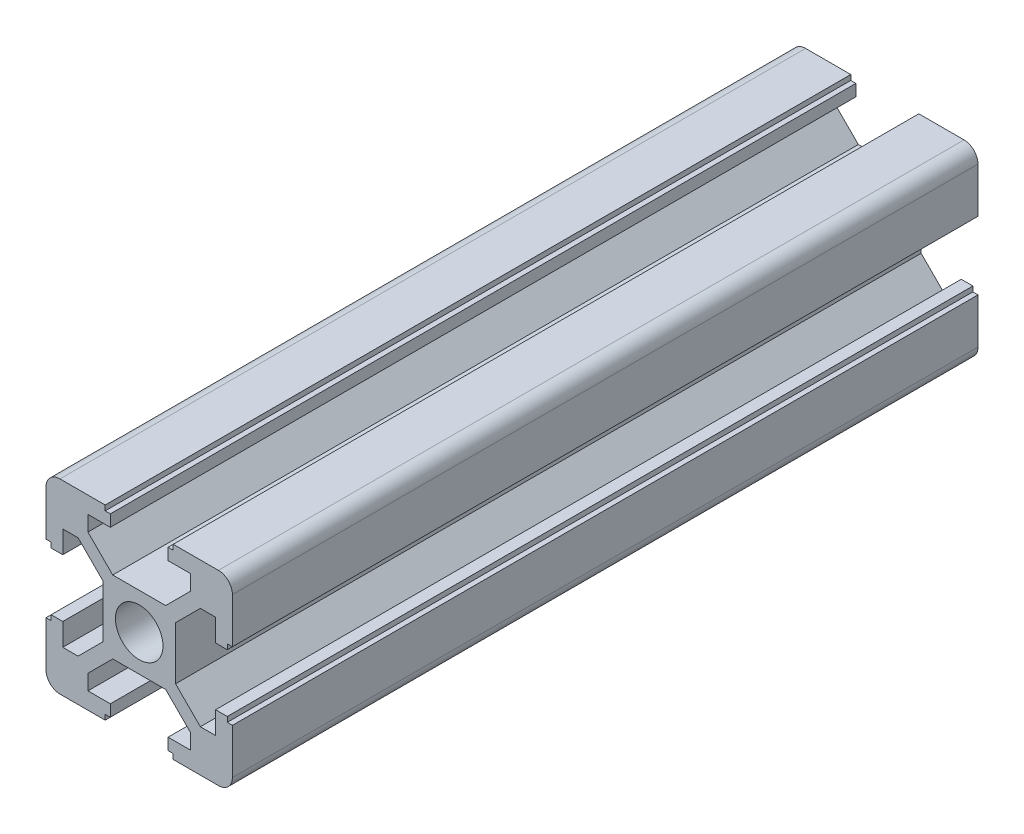
SolidWorks part; units mm, degrees
material "6063-T5"
ref_plane "前视基准面" through (0, 0, 0) normal (0, 0, 1) x (1, 0, 0)
ref_plane "上视基准面" through (0, 0, 0) normal (0, 1, 0) x (1, 0, 0)
ref_plane "右视基准面" through (0, 0, 0) normal (1, 0, 0) x (0, 0, -1)
sketch "草图2" plane through (0, 0, 0) normal (0, 0, 1) x (1, 0, 0)
  line L0 (-3.9, 2.8393) -> (-6.5607, 5.5)
  line L1 (-2.8393, 3.9) -> (2.8393, 3.9)
  line L2 (-3.9, 2.8393) -> (-3.9, -2.8393)
  line L3 (-2.8393, -3.9) -> (2.8393, -3.9)
  line L4 (3.9, 2.8393) -> (3.9, -2.8393)
  line L5 (-3.9, 3.9) -> (3.9, -3.9) construction
  line L6 (-3.9, -3.9) -> (3.9, 3.9) construction
  line L7 (-2.8393, 3.9) -> (-5.5, 6.5607)
  line L8 (-5.5, 6.5607) -> (-5.5, 8.2)
  line L9 (-5.5, 8.2) -> (-3.1, 8.2)
  line L10 (-3.1, 8.2) -> (-3.1, 9.45)
  line L11 (-3.1, 9.45) -> (-3.65, 9.45)
  line L12 (-3.65, 9.45) -> (-3.65, 10)
  line L13 (-3.65, 10) -> (-8.5, 10)
  line L14 (-6.5607, 5.5) -> (-8.2, 5.5)
  line L15 (-10, 3.65) -> (-10, 8.5)
  line L16 (-9.45, 3.65) -> (-10, 3.65)
  line L17 (-9.45, 3.1) -> (-9.45, 3.65)
  line L18 (-8.2, 3.1) -> (-9.45, 3.1)
  line L19 (-8.2, 5.5) -> (-8.2, 3.1)
  line L20 (2.8393, 3.9) -> (5.5, 6.5607)
  line L21 (3.9, 2.8393) -> (6.5607, 5.5)
  line L22 (6.5607, 5.5) -> (8.2, 5.5)
  line L23 (8.2, 5.5) -> (8.2, 3.1)
  line L24 (8.2, 3.1) -> (9.45, 3.1)
  line L25 (9.45, 3.1) -> (9.45, 3.65)
  line L26 (9.45, 3.65) -> (10, 3.65)
  line L27 (10, 3.65) -> (10, 8.5)
  line L28 (5.5, 6.5607) -> (5.5, 8.2)
  line L29 (3.65, 10) -> (8.5, 10)
  line L30 (3.65, 9.45) -> (3.65, 10)
  line L31 (3.1, 9.45) -> (3.65, 9.45)
  line L32 (3.1, 8.2) -> (3.1, 9.45)
  line L33 (5.5, 8.2) -> (3.1, 8.2)
  line L34 (3.9, -2.8393) -> (6.5607, -5.5)
  line L35 (2.8393, -3.9) -> (5.5, -6.5607)
  line L36 (5.5, -6.5607) -> (5.5, -8.2)
  line L37 (5.5, -8.2) -> (3.1, -8.2)
  line L38 (3.1, -8.2) -> (3.1, -9.45)
  line L39 (3.1, -9.45) -> (3.65, -9.45)
  line L40 (3.65, -9.45) -> (3.65, -10)
  line L41 (3.65, -10) -> (8.5, -10)
  line L42 (6.5607, -5.5) -> (8.2, -5.5)
  line L43 (10, -3.65) -> (10, -8.5)
  line L44 (9.45, -3.65) -> (10, -3.65)
  line L45 (9.45, -3.1) -> (9.45, -3.65)
  line L46 (8.2, -3.1) -> (9.45, -3.1)
  line L47 (8.2, -5.5) -> (8.2, -3.1)
  line L48 (-2.8393, -3.9) -> (-5.5, -6.5607)
  line L49 (-3.9, -2.8393) -> (-6.5607, -5.5)
  line L50 (-6.5607, -5.5) -> (-8.2, -5.5)
  line L51 (-8.2, -5.5) -> (-8.2, -3.1)
  line L52 (-8.2, -3.1) -> (-9.45, -3.1)
  line L53 (-9.45, -3.1) -> (-9.45, -3.65)
  line L54 (-9.45, -3.65) -> (-10, -3.65)
  line L55 (-10, -3.65) -> (-10, -8.5)
  line L56 (-5.5, -6.5607) -> (-5.5, -8.2)
  line L57 (-3.65, -10) -> (-8.5, -10)
  line L58 (-3.65, -9.45) -> (-3.65, -10)
  line L59 (-3.1, -9.45) -> (-3.65, -9.45)
  line L60 (-3.1, -8.2) -> (-3.1, -9.45)
  line L61 (-5.5, -8.2) -> (-3.1, -8.2)
  circle A0 centre (0, 0) radius 2.55
  arc A1 (-8.5, 10) -> (-10, 8.5) centre (-8.5, 8.5) ccw
  arc A2 (10, 8.5) -> (8.5, 10) centre (8.5, 8.5) ccw
  arc A3 (8.5, -10) -> (10, -8.5) centre (8.5, -8.5) ccw
  arc A4 (-10, -8.5) -> (-8.5, -10) centre (-8.5, -8.5) ccw
  point P25 (-10, 10)
  point P79 (0, 0)
  dimension "D1" = 5.1
  dimension "D9" = 1.5
  dimension "D2" = 7.8
  dimension "D3" = 1.5
  dimension "D4" = 10
  dimension "D5" = 3.1
  dimension "D6" = 0.55
  dimension "D7" = 1.8
  dimension "D8" = 5.5
  dimension "D11" = 3.9
  dimension "D10" = 4
extrude "凸台-拉伸1" add sketch "草图2" along normal blind 80
